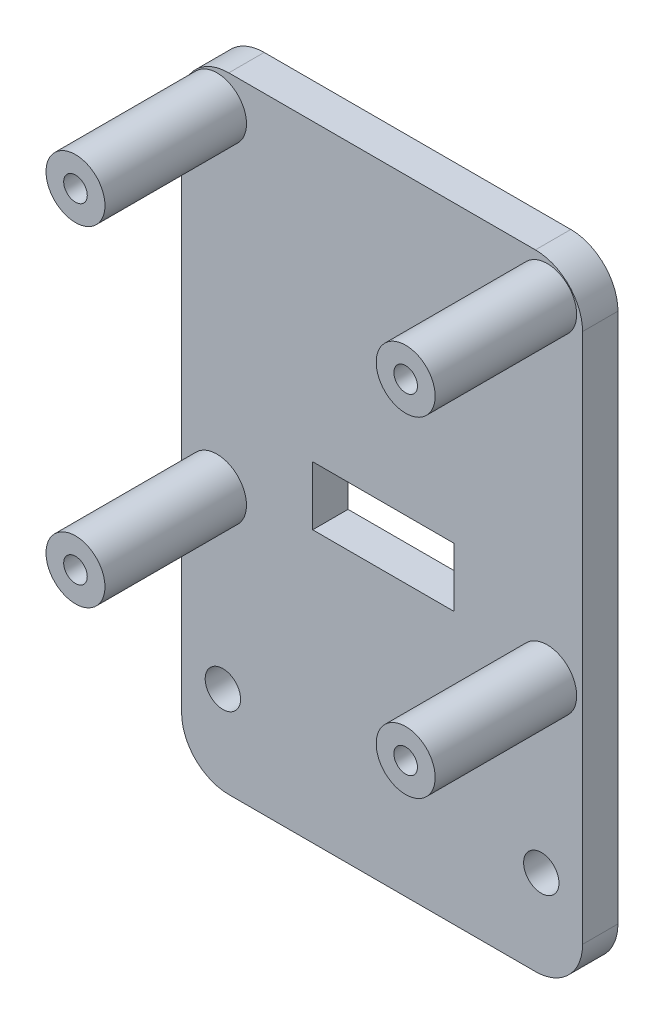
SolidWorks part; units mm, degrees
ref_plane "前视基准面" through (0, 0, 0) normal (0, 0, 1) x (1, 0, 0)
ref_plane "上视基准面" through (0, 0, 0) normal (0, 1, 0) x (1, 0, 0)
ref_plane "右视基准面" through (0, 0, 0) normal (1, 0, 0) x (0, 0, -1)
sketch "草图1" plane through (0, 0, 0) normal (0, 0, 1) x (1, 0, 0)
  line L1 (-17, 7.5) -> (17, 7.5)
  line L2 (-17, 7.5) -> (-17, -7.5)
  line L3 (-17, -7.5) -> (17, -7.5)
  line L4 (17, 7.5) -> (17, -7.5)
  line L5 (-17, 7.5) -> (17, -7.5) construction
  line L6 (-17, -7.5) -> (17, 7.5) construction
  line L7 (-17, 7.5) -> (17, 7.5)
  line L8 (-17, 7.5) -> (-17, 45.5)
  line L9 (-17, 45.5) -> (17, 45.5)
  line L10 (17, 7.5) -> (17, 45.5)
  line L12 (-14, 42.5) -> (14, 42.5)
  line L13 (-14, 42.5) -> (-14, 14.5)
  line L14 (-14, 14.5) -> (14, 14.5)
  line L15 (14, 42.5) -> (14, 14.5)
  line L16 (-14, 42.5) -> (14, 14.5) construction
  line L17 (-14, 14.5) -> (14, 42.5) construction
  circle A0 centre (-13.5, 0) radius 1.5
  circle A1 centre (13.5, 0) radius 1.5
  point P0 (0, 0)
  point P12 (0, 28.5)
  dimension "D3" = 27
  dimension "D1" = 15
  dimension "D2" = 34
  dimension "D4" = 3.5
  dimension "D5" = 38
  dimension "D6" = 28
  dimension "D7" = 28
  dimension "D8" = 3
extrude "凸台-拉伸1" add sketch "草图1" along normal blind 3 contours L1 L10 L9 L8 L12 L15 L14 L13 | L15 L12 L13 L14 | L4 L1 L2 L3 A1 A0
sketch "草图2" plane through (0, 0, 3) normal (0, 0, 1) x (1, 0, 0)
  circle A0 centre (-14, 42.5) radius 2.5
  circle A1 centre (14, 42.5) radius 2.5
  circle A2 centre (-14, 14.5) radius 2.5
  circle A3 centre (14, 14.5) radius 2.5
  dimension "D1" = 5
  dimension "D2" = 5
  dimension "D3" = 5
  dimension "D4" = 5
extrude "凸台-拉伸2" add sketch "草图2" along normal blind 12
sketch "草图3" plane through (0, 0, 15) normal (0, 0, 1) x (1, 0, 0)
  circle A0 centre (-14, 42.5) radius 1
  circle A1 centre (14, 42.5) radius 1
  circle A2 centre (-14, 14.5) radius 1
  circle A3 centre (14, 14.5) radius 1
  point P12 (0, 0)
  dimension "D1" = 2
  dimension "D2" = 2
  dimension "D3" = 2
  dimension "D4" = 2
extrude "切除-拉伸1" cut sketch "草图3" against normal blind 8
fillet "圆角1" radius 4 4 edges at (17, -7.5, 1.5) (-17, -7.5, 1.5) (17, 45.5, 1.5) (-17, 45.5, 1.5)
sketch "草图4" plane through (0, 0, 3) normal (0, 0, 1) x (1, 0, 0)
  line L0 (-13, 45.5) -> (13, 45.5) construction
  line L1 (-5.8858, 20.5) -> (6.1142, 20.5)
  line L2 (-5.8858, 20.5) -> (-5.8858, 15.5)
  line L3 (-5.8858, 15.5) -> (6.1142, 15.5)
  line L4 (6.1142, 20.5) -> (6.1142, 15.5)
  line L5 (-5.8858, 20.5) -> (6.1142, 15.5) construction
  line L6 (-5.8858, 15.5) -> (6.1142, 20.5) construction
  point P0 (0.1142, 18)
  dimension "D1" = 12
  dimension "D2" = 5
  dimension "D3" = 25
extrude "切除-拉伸2" cut sketch "草图4" against normal blind 8
